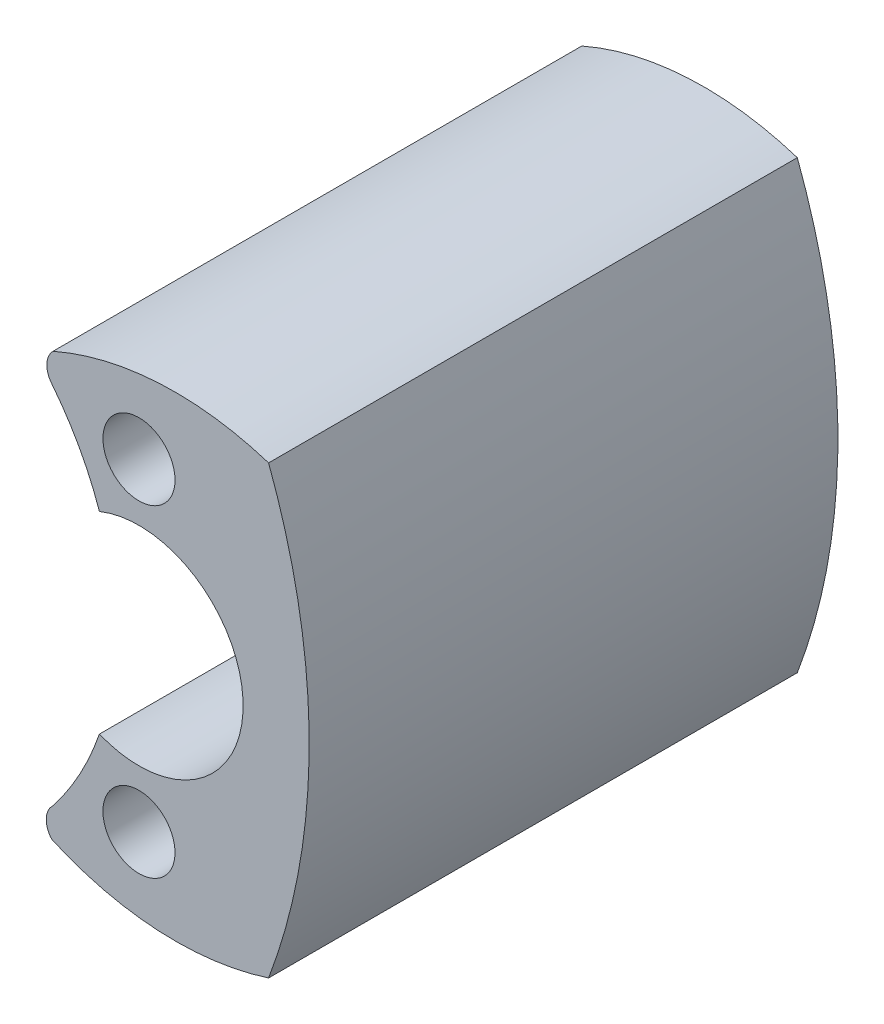
SolidWorks part; units mm, degrees
ref_plane "Front Plane" through (0, 0, 0) normal (0, 0, 1) x (1, 0, 0)
ref_plane "Top Plane" through (0, 0, 0) normal (0, 1, 0) x (1, 0, 0)
ref_plane "Right Plane" through (0, 0, 0) normal (1, 0, 0) x (0, 0, -1)
sketch "Sketch1" plane through (0, 0, 0) normal (0, 0, 1) x (1, 0, 0)
  line L0 (0, 0) -> (0, 9.5) construction
  arc A0 (5.3943, 9.2817) -> (5.3943, -9.2817) centre (-19.2657, 0) cw
  arc A1 (-3.6387, 7.6355) -> (-3.5758, 8.8197) centre (-2.9394, 8.1921) cw
  arc A2 (-3.5758, 8.8197) -> (5.3943, 9.2817) centre (1.5165, -2.7402) cw
  arc A3 (-3.6387, 7.6355) -> (-3.5758, -7.5558) centre (-13.2313, 0) cw
  arc A5 (-3.5758, -7.5558) -> (-3.6256, -8.7977) centre (-2.9797, -8.2016) ccw
  arc A7 (-3.6256, -8.7977) -> (5.3943, -9.2817) centre (1.5165, 2.7402) ccw
extrude "Extrude1" add sketch "Sketch1" along normal blind 22 and the other way blind 0.001
sketch "Sketch3" plane through (0, 0, 22) normal (0, 0, 1) x (1, 0, 0)
  circle A0 centre (0, 6.715) radius 1.5
  circle A1 centre (0, -6.715) radius 1.5
  dimension "D1" = 3
  dimension "D2" = 13.43
extrude "Cut-Extrude1" cut sketch "Sketch3" against normal through all
sketch "Sketch5" plane through (0, 0, -0.001) normal (0, 0, -1) x (-1, 0, 0)
  circle A0 centre (0, 0) radius 4.335
  dimension "D1" = 8.67
extrude "Cut-Extrude2" cut sketch "Sketch5" against normal blind 24
